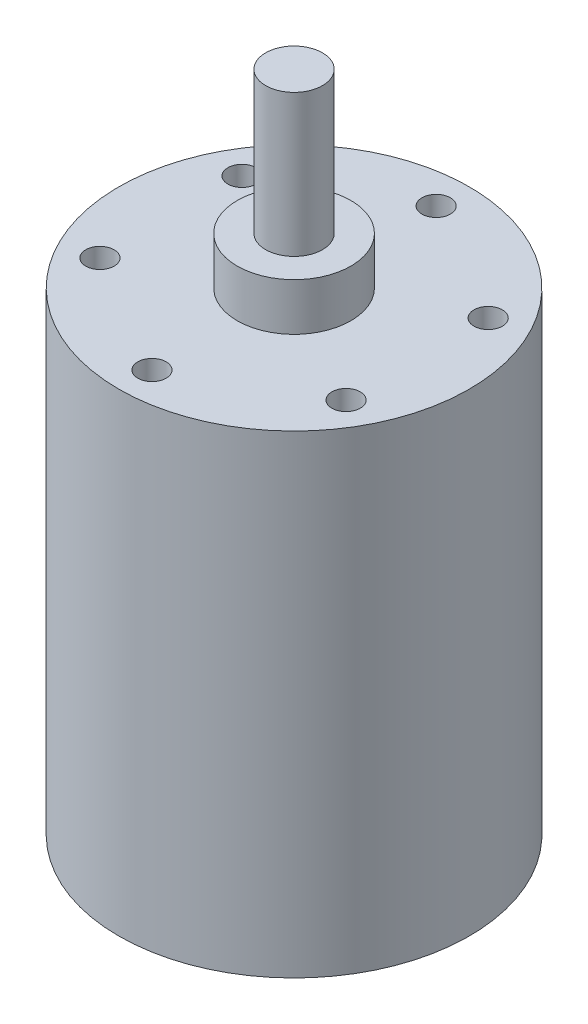
SolidWorks part; units mm, degrees
ref_plane "Front" through (0, 0, 0) normal (0, 0, 1) x (1, 0, 0)
ref_plane "Top" through (0, 0, 0) normal (0, 1, 0) x (1, 0, 0)
ref_plane "Right" through (0, 0, 0) normal (1, 0, 0) x (0, 0, -1)
sketch "Sketch1" plane through (0, 0, 0) normal (0, 1, 0) x (1, 0, 0)
  circle A0 centre (0, 0) radius 18.5
  dimension "D1" = 37
extrude "Boss-Extrude1" add sketch "Sketch1" along normal blind 50
sketch "Sketch2" plane through (0, 50, 0) normal (0, 1, 0) x (1, 0, 0)
  circle A0 centre (0, 0) radius 6
  dimension "D1" = 12
extrude "Boss-Extrude2" add sketch "Sketch2" along normal blind 5
sketch "Sketch3" plane through (0, 55, 0) normal (0, 1, 0) x (1, 0, 0)
  circle A0 centre (0, 0) radius 3
  dimension "D1" = 6
extrude "Boss-Extrude3" add sketch "Sketch3" along normal blind 15
sketch "Sketch4" plane through (0, 50, 0) normal (0, 1, 0) x (1, 0, 0)
  circle A0 centre (0, 15) radius 1.5
  circle A1 centre (12.9904, 7.5) radius 1.5
  circle A2 centre (12.9904, -7.5) radius 1.5
  circle A3 centre (0, -15) radius 1.5
  circle A4 centre (-12.9904, -7.5) radius 1.5
  circle A5 centre (-12.9904, 7.5) radius 1.5
  point P16 (0, 0)
  dimension "D1" = 3
  dimension "D2" = 15
  dimension "D3" = 6
extrude "Cut-Extrude1" cut sketch "Sketch4" against normal blind 10
